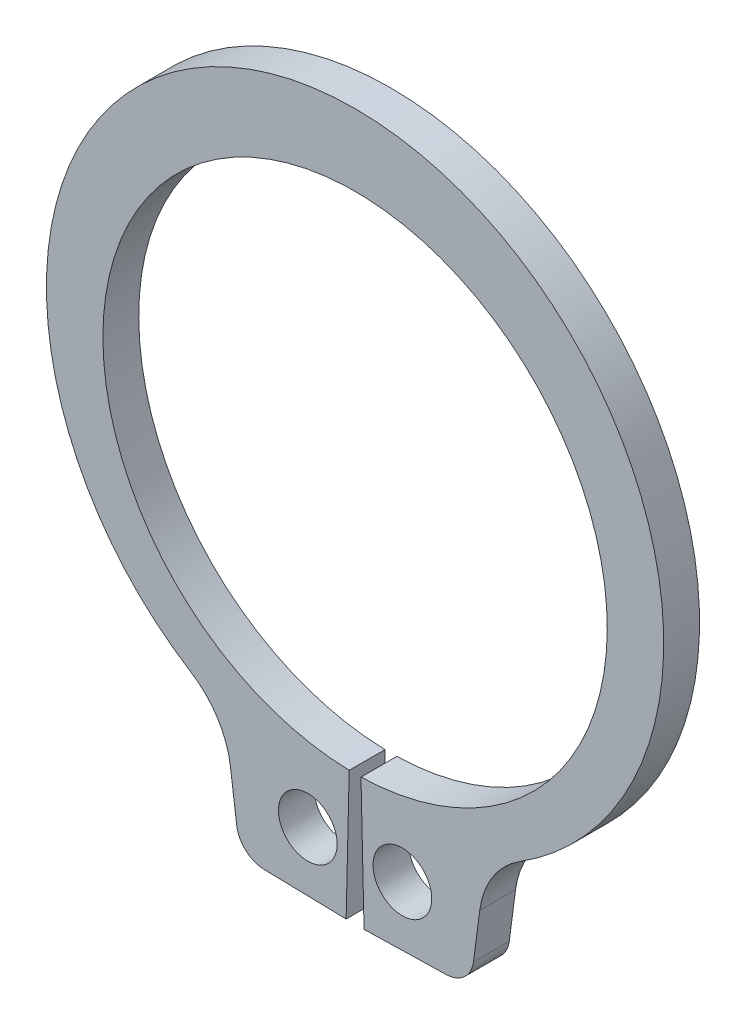
SolidWorks part; units mm, degrees
material "Cast Stainless Steel"
ref_plane "Plane1" through (0, 0, 0) normal (0, 0, 1) x (1, 0, 0)
ref_plane "Plane2" through (0, 0, 0) normal (0, 1, 0) x (1, 0, 0)
ref_plane "Plane3" through (0, 0, 0) normal (1, 0, 0) x (0, 0, -1)
other "Configuration Table"
sketch "Clipboard" plane through (0, 0, 0) normal (0, 0, 1) x (1, 0, 0)
  line L0 (0, 0) -> (1.27, 0)
  line L1 (0, 0) -> (0, 0.7747)
  line L2 (0, 0) -> (0, -2.3114)
  circle A0 centre (0, 0) radius 0.5207
  circle A1 centre (0, 0) radius 4.7625
  dimension "HoleDia" = 1.0414
  dimension "ShaftDia" = 9.525
  dimension "LargeSection" = 1.27
  dimension "SmallSection" = 0.7747
  dimension "LugSection" = 2.3114
sketch "BodySke" plane through (0, 0, 0) normal (0, 0, 1) x (1, 0, 0)
  line L0 (-1.5431, 0) -> (1.5431, 0) construction
  line L1 (0, 0) -> (0, 5.7404) construction
  line L2 (0.1046, -4.4692) -> (0.1588, -6.7799)
  line L3 (-0.1046, -4.4692) -> (-0.1588, -6.7799)
  line L4 (0, 0) -> (3.7331, -5.6618) construction
  line L5 (0, 0) -> (-3.7331, -5.6618) construction
  line L6 (0.1588, -6.7799) -> (1.6141, -6.7459)
  line L7 (2.21, -5.4613) -> (2.0981, -6.3113)
  line L8 (-2.21, -5.4613) -> (-2.0981, -6.3113)
  line L9 (-0.1588, -6.7799) -> (-1.6141, -6.7459)
  circle A0 centre (0, 0) radius 4.4704 construction
  arc A1 (0.1046, -4.4692) -> (-0.1046, -4.4692) centre (0, 0) ccw
  arc A2 (2.8872, -4.3789) -> (-2.8872, -4.3789) centre (0, 0.2688) ccw construction
  arc A3 (0.1588, -6.7799) -> (1.6983, -6.5657) centre (0, 0) ccw construction
  arc A4 (2.9148, -4.3617) -> (2.21, -5.4613) centre (3.7331, -5.6618) ccw
  arc A5 (-2.21, -5.4613) -> (-2.9148, -4.3617) centre (-3.7331, -5.6618) ccw
  arc A6 (-1.6983, -6.5657) -> (-0.1588, -6.7799) centre (0, 0) ccw construction
  arc A7 (2.9148, -4.3617) -> (-2.9148, -4.3617) centre (0, 0.2688) ccw
  arc A8 (-2.228, -5.3248) -> (2.228, -5.3248) centre (0, 0) ccw construction
  circle A9 centre (0.8382, -5.711) radius 0.5207
  circle A10 centre (-0.8382, -5.711) radius 0.5207
  arc A11 (2.0981, -6.3113) -> (1.6141, -6.7459) centre (1.6024, -6.246) cw
  arc A12 (-2.0981, -6.3113) -> (-1.6141, -6.7459) centre (-1.6024, -6.246) ccw
  point P28 (2.0792, -6.4552)
  point P31 (-2.0792, -6.4552)
  dimension "GrooveDia" = 8.9408
  dimension "LugRad" = 6.7818
  dimension "HoleOffsetRad" = 5.7721
  dimension "HoleDia" = 1.0414
  dimension "D3" = 0.5
  dimension "LargeRad" = 5.7404
  dimension "SmallRad" = 5.2451
  dimension "SmallAngle" = 66.798
  dimension "D2" = 15
  dimension "HoleSpacing" = 1.6764
  dimension "Gap" = 0.3175
extrude "Body" add sketch "BodySke" against normal blind 0.635
equation "' \"ShaftDia@Clipboard\" = 4"
equation "' \"Thickness@Body\" = 0.25"
equation "' \"GrooveDia@BodySke\" = 3.8"
equation "' \"LugSection@Clipboard\" = 1.35"
equation "' \"LargeSection@Clipboard\" = 0.65"
equation "' \"SmallSection@Clipboard\" = 0.4"
equation "' \"HoleDia@Clipboard\" = 0.6"
equation "' \"ShaftDia@Clipboard\" = 15"
equation "' \"Thickness@Body\" = 0.9"
equation "' \"GrooveDia@BodySke\" = 14.15"
equation "' \"LugSection@Clipboard\" = 2.8"
equation "' \"LargeSection@Clipboard\" = 1.8"
equation "' \"SmallSection@Clipboard\" = 1.05"
equation "' \"HoleDia@Clipboard\" = 1.2"
equation "\"Gap@BodySke\" =  \"Thickness@Body\" / 2"
equation "\"LargeRad@BodySke\" =  \"GrooveDia@BodySke\" / 2 +  \"LargeSection@Clipboard\""
equation "\"SmallRad@BodySke\" =  \"GrooveDia@BodySke\" / 2 +  \"SmallSection@Clipboard\""
equation "\"LugRad@BodySke\" = \"GrooveDia@BodySke\" / 2 + \"LugSection@Clipboard\""
equation "\"HoleOffsetRad@BodySke\" = (  \"ShaftDia@Clipboard\" / 2 + \"LugRad@BodySke\" ) / 2"
equation "\"HoleSpacing@BodySke\" = \"Gap@BodySke\"  * 2 +  \"HoleDia@Clipboard\""
equation "\"HoleDia@BodySke\" =  \"HoleDia@Clipboard\""
equation "\"SmallAngle@BodySke\" = atn(\"HoleSpacing@BodySke\" / 2 / sqr(\"HoleOffsetRad@BodySke\"  * \"HoleOffsetRad@BodySke\" - (\"HoleSpacing@BodySke\" / 2) * (\"HoleSpacing@BodySke\" / 2) ))  * 8 * ( 180 / 3.141593)"
